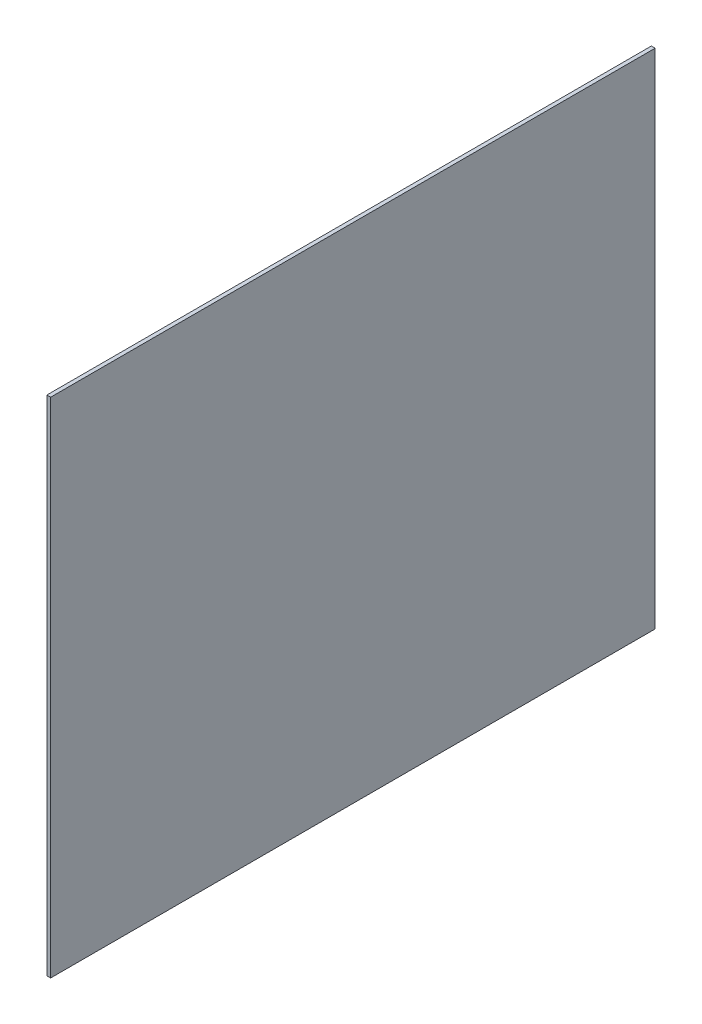
SolidWorks part; units mm, degrees
ref_plane "Front Plane" through (0, 0, 0) normal (0, 0, 1) x (1, 0, 0)
ref_plane "Top Plane" through (0, 0, 0) normal (0, 1, 0) x (1, 0, 0)
ref_plane "Right Plane" through (0, 0, 0) normal (1, 0, 0) x (0, 0, -1)
sketch "Sketch1" plane through (0, 0, 0) normal (0, 0, 1) x (1, 0, 0)
  line L1 (-12.5, -1664.1598) -> (12.5, -1664.1598)
  line L2 (-12.5, -1664.1598) -> (-12.5, 1664.1598)
  line L3 (-12.5, 1664.1598) -> (12.5, 1664.1598)
  line L4 (12.5, -1664.1598) -> (12.5, 1664.1598)
extrude "Boss-Extrude1" add sketch "Sketch1" along normal blind 4000 from offset 2000
